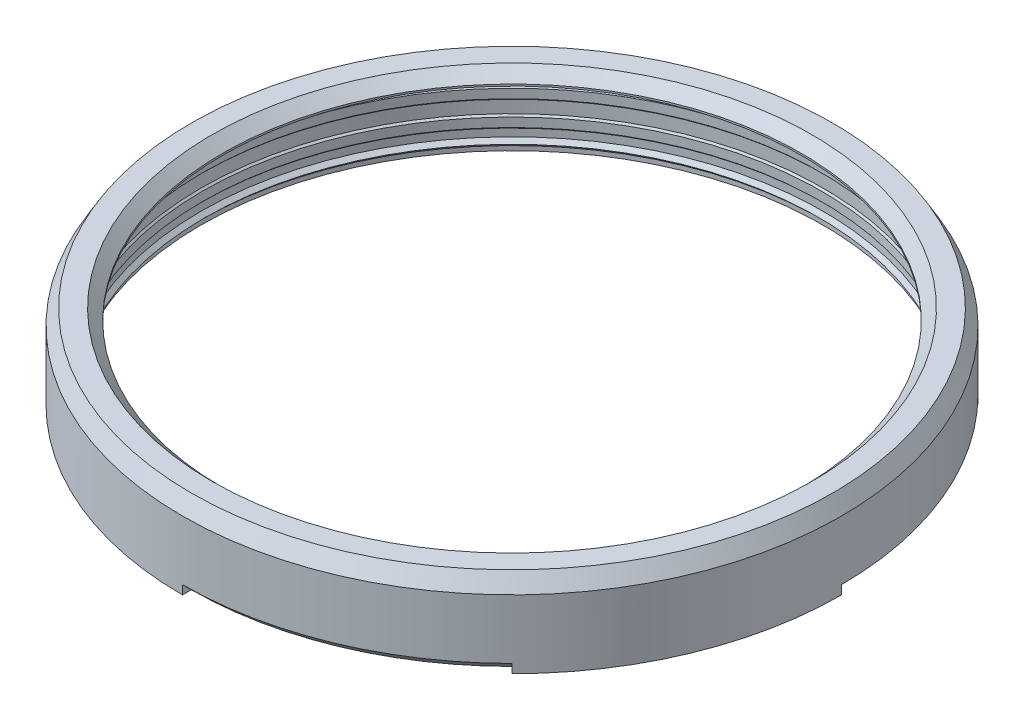
SolidWorks part; units mm, degrees
ref_plane "前视基准面" through (0, 0, 0) normal (0, 0, 1) x (1, 0, 0)
ref_plane "上视基准面" through (0, 0, 0) normal (0, 1, 0) x (1, 0, 0)
ref_plane "右视基准面" through (0, 0, 0) normal (1, 0, 0) x (0, 0, -1)
sketch "草图1" plane through (0, 0, 0) normal (0, 1, 0) x (1, 0, 0)
  circle A0 centre (0, 0) radius 37
  dimension "D1" = 74
extrude "凸台-拉伸1" add sketch "草图1" along normal blind 2
sketch "草图3" plane through (0, 0, 0) normal (0.809, 0, 0.5878) x (0.5878, 0, -0.809)
  line L0 (34.93, -8) -> (34.93, -7.5)
  line L1 (34.93, -7.5) -> (34.505, -7.075)
  line L2 (34.505, -7.075) -> (34.93, -6.65)
  line L3 (34.93, -6.65) -> (34.93, -5.8)
  line L4 (34.93, -5.8) -> (34.74, -5.61)
  line L5 (34.74, -5.61) -> (34.74, -4.59)
  line L6 (34.74, -4.59) -> (34.93, -4.4)
  line L7 (34.93, -4.4) -> (34.93, -3)
  line L8 (34.93, -3) -> (34.74, -2.81)
  line L9 (34.74, -2.81) -> (34.74, -1.79)
  line L10 (34.74, -1.79) -> (34.93, -1.6)
  line L11 (34.93, -1.6) -> (34.93, -1.4)
  line L12 (33.53, 0) -> (37, 0)
  line L13 (37, 0) -> (37, -8)
  line L14 (37, -8) -> (34.93, -8)
  line L15 (34.8, -8) -> (36, -8) construction
  line L16 (34.8, -8) -> (34.8, -7.5) construction
  line L17 (0, 0) -> (0, 10.6202) construction
  arc A0 (34.93, -1.4) -> (33.53, 0) centre (33.53, -1.4) ccw
  dimension "D9" = 1.4
  dimension "D1" = 2.26
  dimension "D2" = 8
  dimension "D3" = 0.5
  dimension "D4" = 0.85
  dimension "D5" = 1.4
  dimension "D6" = 1.02
  dimension "D7" = 1.02
  dimension "D8" = 0.2
  dimension "D10" = 135
  dimension "D11" = 0.13
revolve "旋转1" add sketch "草图3" angle 360 about L17
sketch "草图4" plane through (0, 2, 0) normal (0, 1, 0) x (1, 0, 0)
  circle A0 centre (0, 0) radius 32.5
  circle A1 centre (0, 0) radius 37 construction
  dimension "D1" = 4.5
extrude "切除-拉伸1" cut sketch "草图4" against normal through all
sketch "草图5" plane through (0, 2, 0) normal (0, 1, 0) x (1, 0, 0)
  circle A1 centre (0, 0) radius 37
  circle A2 centre (0, 0) radius 37
  dimension "D1" = 0
extrude "切除-拉伸2" cut sketch "草图5" against normal blind 0.6
chamfer "倒角1" distance 1.2 angle 45 1 edges at (0, 1.4, 32.5)
chamfer "倒角2" distance 1.732 angle 30 1 edges at (0, 1.4, 37)
sketch "草图6" plane through (0, 0, 0) normal (0, 0, 1) x (1, 0, 0)
  line L0 (37, -8) -> (37, -7)
  line L1 (37, -7) -> (36, -8)
  line L2 (30.4056, -8) -> (43, -8) construction
  line L3 (36, -8) -> (37, -8)
  line L4 (0, 0) -> (0, 11.8797) construction
  dimension "D1" = 1
  dimension "D2" = 1
revolve "切除-旋转1" cut sketch "草图6" angle 45 about L4
pattern_circular "阵列(圆周)1" count 4 over 360 about axis through (0, 0, 0) along (0, 1, 0) of "切除-旋转1"
sketch "草图7" plane through (0, 0, 0) normal (0, -1, 0) x (1, 0, 0)
  circle A0 centre (0, 0) radius 33.32
  circle A1 centre (0, 0) radius 33.78
  circle A2 centre (0, 0) radius 32.5 construction
  dimension "D1" = 0.82
  dimension "D2" = 0.46
extrude "凸台-拉伸2" add sketch "草图7" along normal blind 0.5
